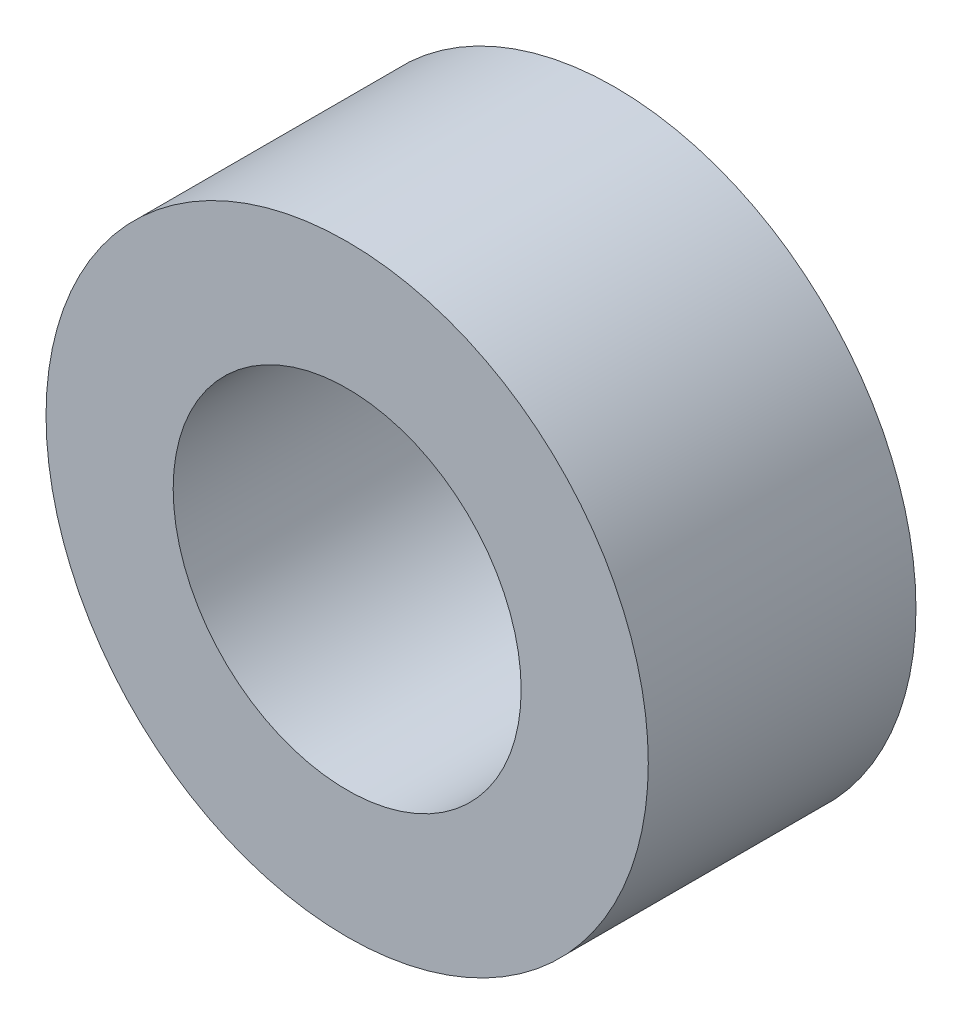
SolidWorks part; units mm, degrees
ref_plane "Front Plane" through (0, 0, 0) normal (0, 0, 1) x (1, 0, 0)
ref_plane "Top Plane" through (0, 0, 0) normal (0, 1, 0) x (1, 0, 0)
ref_plane "Right Plane" through (0, 0, 0) normal (1, 0, 0) x (0, 0, -1)
sketch "Sketch1" plane through (0, 0, 0) normal (0, 0, 1) x (1, 0, 0)
  circle A0 centre (0, 0) radius 4.5
  dimension "D1" = 9
extrude "Boss-Extrude1" add sketch "Sketch1" along normal blind 4
sketch "Sketch2" plane through (0, 0, 4) normal (0, 0, 1) x (1, 0, 0)
  circle A0 centre (0, 0) radius 2.6
  dimension "D1" = 5.2
extrude "Cut-Extrude1" cut sketch "Sketch2" against normal through all
